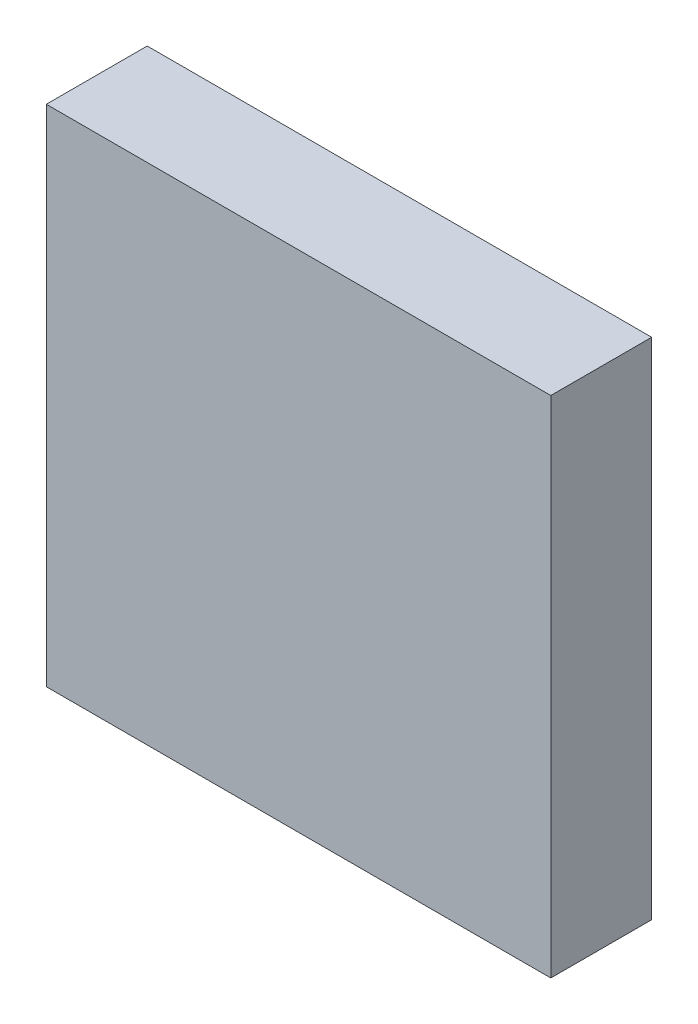
SolidWorks part; units mm, degrees
ref_plane "Front Plane" through (0, 0, 0) normal (0, 0, 1) x (1, 0, 0)
ref_plane "Top Plane" through (0, 0, 0) normal (0, 1, 0) x (1, 0, 0)
ref_plane "Right Plane" through (0, 0, 0) normal (1, 0, 0) x (0, 0, -1)
sketch "Sketch1" plane through (0, 0, 0) normal (0, 1, 0) x (1, 0, 0)
  line L1 (-500, -100) -> (500, -100)
  line L2 (-500, -100) -> (-500, 100)
  line L3 (-500, 100) -> (500, 100)
  line L4 (500, -100) -> (500, 100)
  line L5 (0, 100) -> (0, -100) construction
  line L6 (-500, 0) -> (500, 0) construction
  point P0 (0, 0)
  dimension "D1" = 1000
  dimension "D2" = 200
extrude "Boss-Extrude1" add sketch "Sketch1" along normal blind 1000
